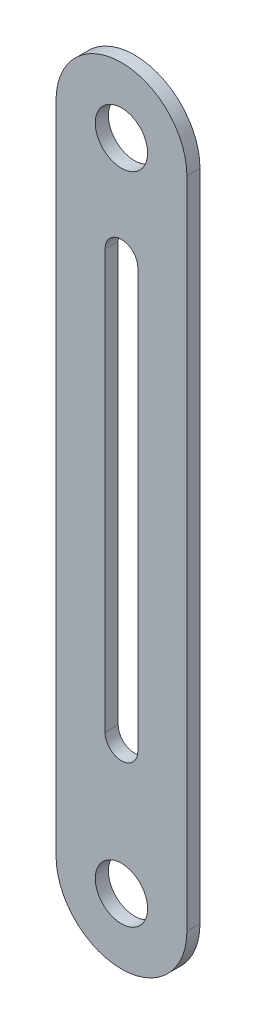
SolidWorks part; units mm, degrees
ref_plane "前视基准面" through (0, 0, 0) normal (0, 0, 1) x (1, 0, 0)
ref_plane "上视基准面" through (0, 0, 0) normal (0, 1, 0) x (1, 0, 0)
ref_plane "右视基准面" through (0, 0, 0) normal (1, 0, 0) x (0, 0, -1)
sketch "草图1" plane through (0, 0, 0) normal (0, 0, 1) x (1, 0, 0)
  line L0 (0, 0) -> (0, -200) construction
  line L3 (-20, 0) -> (-20, -200)
  line L5 (20, -200) -> (20, 0)
  circle A4 centre (0, 0) radius 8
  arc A5 (20, 0) -> (-20, 0) centre (0, 0) ccw
  arc A6 (-20, -200) -> (20, -200) centre (0, -200) ccw
  circle A7 centre (0, -200) radius 8
  dimension "D1" = 16
  dimension "D3" = 200
  dimension "D4" = 40
  dimension "D5" = 16
  dimension "D2" = 40
extrude "凸台-拉伸1" add sketch "草图1" along normal blind 4
sketch "草图2" plane through (0, 0, 4) normal (0, 0, 1) x (1, 0, 0)
  line L13 (-5, 0) -> (-5, -200)
  line L14 (5, -200) -> (5, 0)
  line L15 (-5, -31.845) -> (-5, -159.845)
  line L16 (5, -159.845) -> (5, -31.845)
  arc A3 (-5, -31.845) -> (5, -31.845) centre (0, -31.845) cw
  arc A8 (-5, -200) -> (5, -200) centre (0, -200) ccw
  arc A10 (-5, -159.845) -> (5, -159.845) centre (0, -159.845) ccw
  dimension "D1" = 15
extrude "切除-拉伸2" cut sketch "草图2" against normal through all
